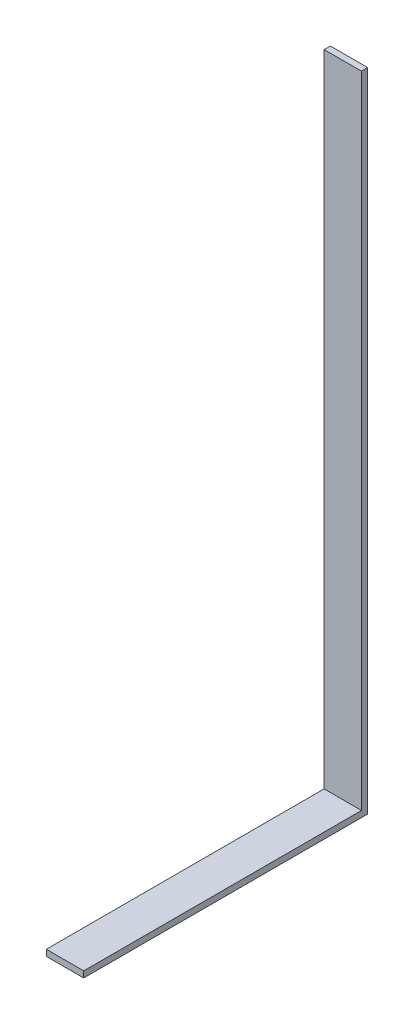
SolidWorks part; units mm, degrees
ref_plane "Alzado" through (0, 0, 0) normal (0, 0, 1) x (1, 0, 0)
ref_plane "Planta" through (0, 0, 0) normal (0, 1, 0) x (1, 0, 0)
ref_plane "Vista lateral" through (0, 0, 0) normal (1, 0, 0) x (0, 0, -1)
sketch "Croquis1" plane through (0, 0, 0) normal (0, 0, 1) x (1, 0, 0)
  line L1 (-19.05, 3.155) -> (19.05, 3.155)
  line L2 (-19.05, 3.155) -> (-19.05, -3.155)
  line L3 (-19.05, -3.155) -> (19.05, -3.155)
  line L4 (19.05, 3.155) -> (19.05, -3.155)
  line L5 (-19.05, 3.155) -> (19.05, -3.155) construction
  line L6 (-19.05, -3.155) -> (19.05, 3.155) construction
  point P0 (0, 0)
  dimension "D1" = 38.1
  dimension "D2" = 6.31
extrude "Saliente-Extruir1" add sketch "Croquis1" along normal blind 289.39
sketch "Croquis3" plane through (0, -3.155, 0) normal (0, -1, 0) x (1, 0, 0)
  line L0 (-19.05, 289.39) -> (-19.05, 0) construction
  line L1 (19.05, 0) -> (-19.05, 0)
  line L2 (19.05, 0) -> (19.05, 6.31)
  line L3 (19.05, 6.31) -> (-19.05, 6.31)
  line L4 (-19.05, 0) -> (-19.05, 6.31)
  line L5 (19.05, 0) -> (-19.05, 6.31) construction
  line L6 (19.05, 6.31) -> (-19.05, 0) construction
  line L7 (19.05, 289.39) -> (19.05, 0) construction
  line L8 (-19.05, 0) -> (19.05, 0) construction
  point P0 (0, 3.155)
  dimension "D1" = 6.31
extrude "Saliente-Extruir2" add sketch "Croquis3" against normal blind 658.79
